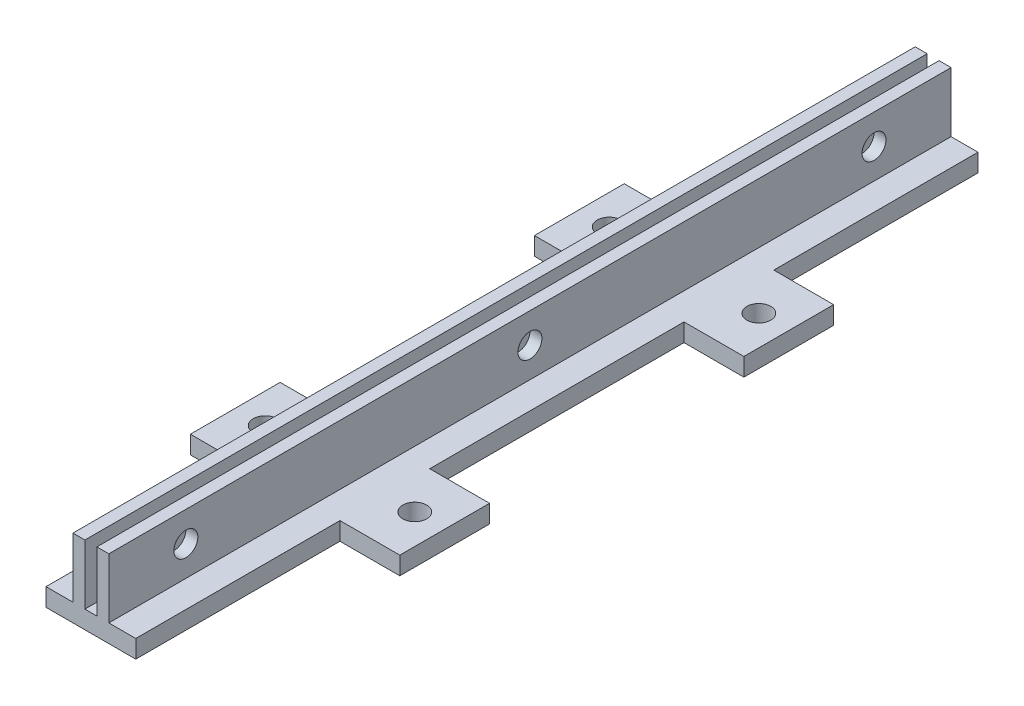
SolidWorks part; units mm, degrees
ref_plane "Front Plane" through (0, 0, 0) normal (0, 0, 1) x (1, 0, 0)
ref_plane "Top Plane" through (0, 0, 0) normal (0, 1, 0) x (1, 0, 0)
ref_plane "Right Plane" through (0, 0, 0) normal (1, 0, 0) x (0, 0, -1)
sketch "Sketch1" plane through (0, 0, 0) normal (0, 1, 0) x (1, 0, 0)
  line L0 (0, 0) -> (-17.5, 0) construction
  line L1 (0, 0) -> (0, 176.2485) construction
  line L2 (0, 0) -> (17.5, 0) construction
  line L3 (0, 0) -> (0, -104.9519) construction
  line L4 (-27.5, 42.8738) -> (-27.5, 13.75)
  line L5 (-27.5, 85) -> (27.5, 85)
  line L6 (-27.5, 85) -> (-27.5, 70.3738)
  line L7 (-27.5, -85) -> (27.5, -85)
  line L8 (27.5, 85) -> (27.5, 70.3738)
  line L9 (-27.5, -13.75) -> (-27.5, -42.8738)
  line L11 (-27.5, -70.3738) -> (-27.5, -85)
  line L12 (27.5, 42.8738) -> (27.5, 13.75)
  line L13 (27.5, -13.75) -> (27.5, -42.8738)
  line L14 (27.5, -70.3738) -> (27.5, -85)
  arc A1 (-27.5, 42.8738) -> (-27.5, 70.3738) centre (-27.5, 56.6238) ccw
  arc A2 (-27.5, -42.8738) -> (-27.5, -70.3738) centre (-27.5, -56.6238) cw
  arc A3 (27.5, -42.8738) -> (27.5, -70.3738) centre (27.5, -56.6238) ccw
  arc A5 (27.5, 42.8738) -> (27.5, 70.3738) centre (27.5, 56.6238) cw
  arc A7 (-27.5, -13.75) -> (-27.5, 13.75) centre (-27.5, 0) ccw
  arc A8 (27.5, -13.75) -> (27.5, 13.75) centre (27.5, 0) cw
  dimension "D6" = 27.5
  dimension "D3" = 27.5
  dimension "D1" = 170
  dimension "D2" = 55
  dimension "D4" = 85
  dimension "D7" = 57.5
extrude "Boss-Extrude1" add sketch "Sketch1" along normal blind 5
sketch "Sketch2" plane through (0, 5, 0) normal (0, 1, 0) x (1, 0, 0)
  line L0 (0, 85) -> (0, 90.6729) construction
  line L1 (27.5, 85) -> (-27.5, 85) construction
  line L2 (-7.5, 85) -> (7.5, 85)
  line L3 (-7.5, 85) -> (-7.5, 36.25)
  line L4 (-7.5, -85) -> (7.5, -85)
  line L5 (7.5, 85) -> (7.5, 36.25)
  line L6 (-27.5, -85) -> (27.5, -85) construction
  line L7 (0, 0) -> (75.9549, 0) construction
  line L8 (-7.5, 36.25) -> (-17.5, 36.25)
  line L10 (-7.5, 21.25) -> (-17.5, 21.25)
  line L11 (-17.5, 36.25) -> (-17.5, 21.25)
  line L12 (-7.5, -21.25) -> (-17.5, -21.25)
  line L13 (-17.5, -36.25) -> (-17.5, -21.25)
  line L14 (-7.5, -36.25) -> (-17.5, -36.25)
  line L17 (7.5, -36.25) -> (17.5, -36.25)
  line L18 (17.5, -36.25) -> (17.5, -21.25)
  line L19 (7.5, -21.25) -> (17.5, -21.25)
  line L20 (7.5, 21.25) -> (17.5, 21.25)
  line L21 (17.5, 36.25) -> (17.5, 21.25)
  line L22 (7.5, 36.25) -> (17.5, 36.25)
  line L24 (-7.5, 21.25) -> (-7.5, -21.25)
  line L25 (7.5, 21.25) -> (7.5, -21.25)
  line L26 (-7.5, -36.25) -> (-7.5, -85)
  line L27 (7.5, -36.25) -> (7.5, -85)
  arc A0 (-27.5, 42.8738) -> (-27.5, 70.3738) centre (-27.5, 56.6238) ccw construction
  arc A1 (27.5, 70.3738) -> (27.5, 42.8738) centre (27.5, 56.6238) ccw construction
  dimension "D1" = 20
  dimension "D2" = 20
  dimension "D3" = 10
  dimension "D4" = 15
  dimension "D5" = 21.25
extrude "Boss-Extrude2" add sketch "Sketch2" along normal blind 3
sketch "Sketch3" plane through (0, 8, 0) normal (0, 1, 0) x (1, 0, 0)
  line L0 (0, 0) -> (0, 90.0021) construction
  line L1 (7.5, 85) -> (-7.5, 85) construction
  line L7 (27.5, 85) -> (-27.5, 85) construction
  line L8 (-1, -85) -> (-3, -85)
  line L9 (-1, -85) -> (-1, 85)
  line L10 (-1, 85) -> (-3, 85)
  line L11 (-3, -85) -> (-3, 85)
  line L12 (1, -85) -> (3, -85)
  line L13 (1, -85) -> (1, 85)
  line L14 (1, 85) -> (3, 85)
  line L15 (3, -85) -> (3, 85)
  dimension "D3" = 2
extrude "Boss-Extrude3" add sketch "Sketch3" along normal blind 10
sketch "Sketch5" plane through (-3, 0, 0) normal (-1, 0, 0) x (0, 0, 1)
  line L0 (0, 0) -> (0, 33.4762) construction
  line L2 (-85, 18) -> (85, 18) construction
  line L3 (0, 13) -> (68.8382, 13) construction
  line L4 (0, 13) -> (-69.2306, 13) construction
  circle A0 centre (0, 13) radius 2
  circle A1 centre (-57.5, 13) radius 2
  circle A2 centre (57.5, 13) radius 2
  dimension "D1" = 4
  dimension "D3" = 4
  dimension "D2" = 5
  dimension "D4" = 57.5
extrude "Cut-Extrude1" cut sketch "Sketch5" against normal blind 10
sketch "Sketch6" plane through (0, 8, 0) normal (0, 1, 0) x (1, 0, 0)
  line L0 (0, 0) -> (25.4708, 0) construction
  line L1 (0, 0) -> (0, 34.8017) construction
  line L2 (-7.5, 36.25) -> (-17.5, 36.25) construction
  line L3 (-17.5, 36.25) -> (-17.5, 21.25) construction
  circle A0 centre (-12.5, 28.75) radius 2
  circle A1 centre (12.5, 28.75) radius 2
  circle A2 centre (12.5, -28.75) radius 2
  circle A3 centre (-12.5, -28.75) radius 2
  dimension "D1" = 4
  dimension "D2" = 7.5
  dimension "D3" = 5
extrude "Cut-Extrude3" cut sketch "Sketch6" against normal blind 5
sketch "Sketch8" plane through (0, 18, 0) normal (0, 1, 0) x (1, 0, 0)
  line L0 (0, 0) -> (57.6726, 0) construction
  line L1 (-27.5, 85) -> (27.5, 85)
  line L2 (-27.5, 85) -> (-27.5, 70.3738)
  line L3 (-27.5, 70.3738) -> (27.5, 70.3738)
  line L4 (27.5, 85) -> (27.5, 70.3738)
  line L5 (-27.5, -70.3738) -> (27.5, -70.3738)
  line L6 (27.5, -85) -> (27.5, -70.3738)
  line L7 (-27.5, -85) -> (27.5, -85)
  line L8 (-27.5, -85) -> (-27.5, -70.3738)
extrude "Cut-Extrude4" cut sketch "Sketch8" against normal blind 20
sketch "Sketch9" plane through (-27.5, 0, 0) normal (-1, 0, 0) x (0, 0, 1)
  line L1 (-70.3738, 0) -> (70.3738, 0)
  line L2 (-70.3738, 0) -> (-70.3738, 5)
  line L3 (-70.3738, 5) -> (70.3738, 5)
  line L4 (70.3738, 0) -> (70.3738, 5)
extrude "Cut-Extrude5" cut sketch "Sketch9" against normal blind 300
